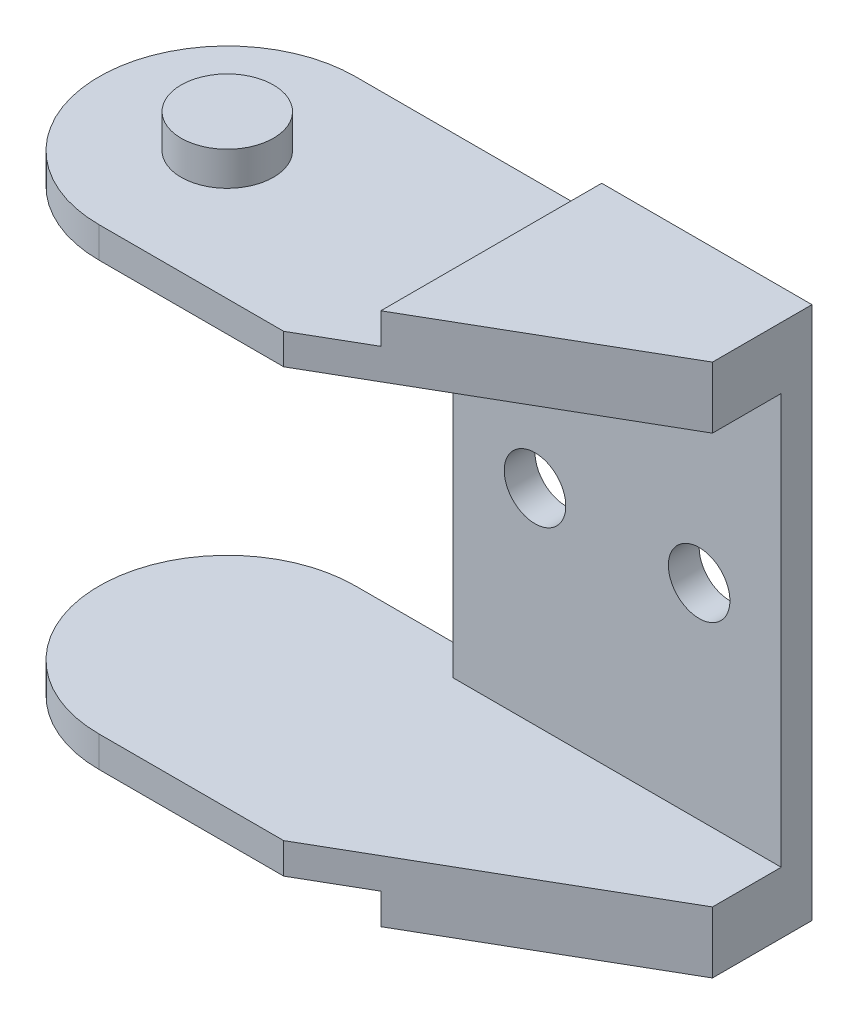
SolidWorks part; units mm, degrees
ref_plane "Front" through (0, 0, 0) normal (0, 0, 1) x (1, 0, 0)
ref_plane "Top" through (0, 0, 0) normal (0, 1, 0) x (1, 0, 0)
ref_plane "Right" through (0, 0, 0) normal (1, 0, 0) x (0, 0, -1)
sketch "Sketch1" plane through (0, 0, 0) normal (0, 1, 0) x (1, 0, 0)
  line L0 (9, -6.25) -> (22.25, 1.3999)
  line L1 (22.25, 1.3999) -> (22.25, 6.25)
  line L2 (22.25, 6.25) -> (0, 6.25)
  line L3 (0, -6.25) -> (9, -6.25)
  arc A0 (0, 6.25) -> (0, -6.25) centre (0, 0) ccw
  dimension "D1" = 6.25
  dimension "D2" = 22.25
  dimension "D3" = 9
  dimension "D4" = 30
extrude "Boss-Extrude1" add sketch "Sketch1" against normal mid plane 26
sketch "Sketch2" plane through (0, 0, 0) normal (0, 1, 0) x (1, 0, 0)
  line L0 (6.25, 4.75) -> (6.25, 6.25)
  line L1 (22.25, 1.3999) -> (22.25, 6.25) construction
  line L2 (6.25, 6.25) -> (-6.25, 6.25)
  line L3 (-6.25, 6.25) -> (-6.25, -6.25)
  line L4 (22.25, -6.25) -> (22.25, 4.75)
  line L5 (22.25, 4.75) -> (6.25, 4.75)
  line L6 (-6.25, -6.25) -> (22.25, -6.25)
  line L9 (22.25, 6.25) -> (0, 6.25) construction
  line L10 (0, -6.25) -> (9, -6.25) construction
  arc A0 (0, 6.25) -> (0, -6.25) centre (0, 0) ccw construction
  dimension "D1" = 1.5
  dimension "D2" = 16
extrude "Cut-Extrude1" cut sketch "Sketch2" against normal mid plane 20
sketch "Sketch3" plane through (0, 13, 0) normal (0, 1, 0) x (-1, 0, 0)
  line L0 (-12, -6.25) -> (6.25, -6.25)
  line L1 (6.25, 6.25) -> (-12, 6.25)
  line L2 (0, 6.25) -> (-9, 6.25) construction
  line L3 (-12, 6.25) -> (-12, -6.25)
  line L4 (-22.25, -1.3999) -> (-22.25, -6.25) construction
  line L5 (-22.25, -6.25) -> (0, -6.25) construction
  line L6 (6.25, -6.25) -> (6.25, 6.25)
  arc A0 (0, -6.25) -> (0, 6.25) centre (0, 0) ccw construction
  dimension "D1" = 10.25
extrude "Cut-Extrude2" cut sketch "Sketch3" against normal blind 1.5
mirror "Mirror1" about plane through (0, 0, 0) normal (0, 1, 0) of "Cut-Extrude2"
sketch "Sketch7" plane through (0, 11.5, 0) normal (0, 1, 0) x (-1, 0, 0)
  circle A0 centre (0, 0) radius 2.25
  dimension "D1" = 4.5
extrude "Boss-Extrude2" add sketch "Sketch7" along normal blind 1.65
mirror "Mirror2" about plane through (0, 0, 0) normal (0, 1, 0) of "Boss-Extrude2"
hole_wizard "Ø3.0 (3) Diameter Hole1" positions "Sketch13" profile "Sketch12" hole size "Ø3.0" standard "ANSI Metric"
sketch "Sketch13" plane through (0, 0, -6.25) normal (0, 0, -1) x (-1, 0, 0)
  line L0 (-18.25, 0) -> (-22.25, 0) construction
  line L1 (-22.25, -13) -> (-22.25, 13) construction
  point P0 (-10.25, 0)
  point P1 (-18.25, 0)
  dimension "D1" = 8
  dimension "D2" = 4
sketch "Sketch12" plane through (10.25, 0, -6.25) normal (1, 0, 0) x (0, 1, 0)
  line L0 (0, 0) -> (0, 12.5)
  line L1 (0, 12.5) -> (1.5, 12.5)
  line L2 (1.5, 12.5) -> (1.5, 0)
  line L5 (1.5, 0) -> (0, 0)
  line L11 (0, -6.35) -> (0, 107.95) construction
  dimension "Thru Hole Dia." = 3
  dimension "Thru Hole Depth" = 12.5
